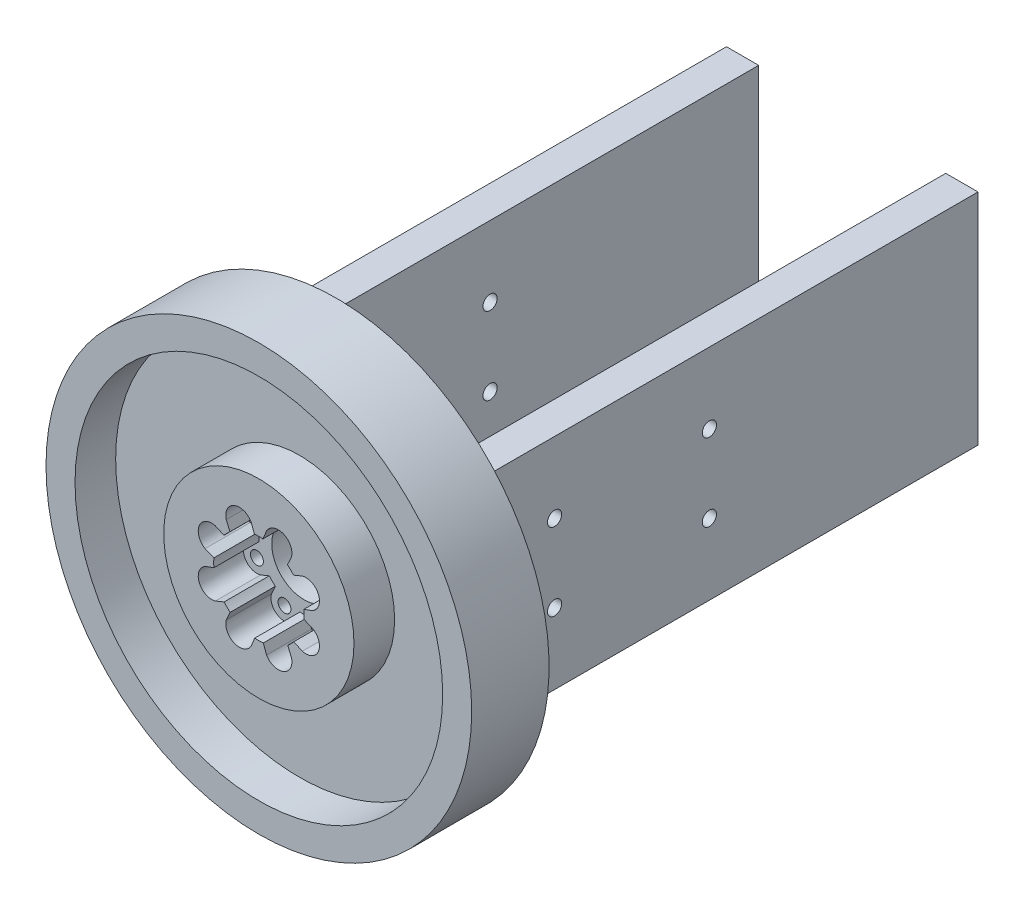
SolidWorks part; units mm, degrees
ref_plane "Alzado" through (0, 0, 0) normal (0, 0, 1) x (1, 0, 0)
ref_plane "Planta" through (0, 0, 0) normal (0, 1, 0) x (1, 0, 0)
ref_plane "Vista lateral" through (0, 0, 0) normal (1, 0, 0) x (0, 0, -1)
sketch "Croquis1" plane through (0, 0, 0) normal (0, 0, 1) x (1, 0, 0)
  circle A0 centre (0, 0) radius 33
  dimension "D1" = 66
extrude "Saliente-Extruir3" add sketch "Croquis1" along normal blind 10
sketch "Croquis6" plane through (0, 0, 0) normal (0, 0, -1) x (-1, 0, 0)
  circle A1 centre (0, 0) radius 28 construction
  circle A2 centre (0, 28) radius 1.5
  circle A3 centre (24.2487, 14) radius 1.5
  circle A4 centre (24.2487, -14) radius 1.5
  circle A5 centre (0, -28) radius 1.5
  circle A6 centre (-24.2487, -14) radius 1.5
  circle A7 centre (-24.2487, 14) radius 1.5
  dimension "D1" = 56
  dimension "D2" = 3
  dimension "D3" = 6
extrude "Cortar-Extruir4" cut sketch "Croquis6" against normal blind 2
sketch "Croquis7" plane through (0, 0, 0) normal (0, 0, -1) x (-1, 0, 0)
  circle A0 centre (0, 0) radius 11
  circle A1 centre (0, 0) radius 33
  circle A2 centre (0, 0) radius 33
  circle A3 centre (24.2487, -14) radius 1.5 construction
  circle A4 centre (0, -28) radius 1.5 construction
  circle A5 centre (-24.2487, -14) radius 1.5 construction
  circle A6 centre (24.2487, 14) radius 1.5 construction
  circle A7 centre (0, 28) radius 1.5 construction
  circle A8 centre (-24.2487, 14) radius 1.5 construction
  circle A9 centre (24.2487, -14) radius 1.5
  circle A10 centre (0, -28) radius 1.5
  circle A11 centre (-24.2487, -14) radius 1.5
  circle A12 centre (24.2487, 14) radius 1.5
  circle A13 centre (0, 28) radius 1.5
  circle A14 centre (-24.2487, 14) radius 1.5
  dimension "D2" = 22
  dimension "D1" = 0
extrude "Saliente-Extruir5" add sketch "Croquis7" along normal blind 2
sketch "Croquis8" plane through (0, 0, -2) normal (0, 0, -1) x (-1, 0, 0)
  line L0 (0, 33) -> (0, -33) construction
  line L1 (14.5, 0) -> (-14.5, 0) construction
  line L3 (-19.5, -17) -> (-14.5, -17)
  line L4 (-19.5, -17) -> (-19.5, 17)
  line L5 (-19.5, 17) -> (-14.5, 17)
  line L6 (-14.5, -17) -> (-14.5, 17)
  line L7 (14.5, -17) -> (19.5, -17)
  line L8 (14.5, -17) -> (14.5, 17)
  line L9 (14.5, 17) -> (19.5, 17)
  line L10 (19.5, -17) -> (19.5, 17)
  circle A0 centre (0, 0) radius 33 construction
  point P8 (0, 0)
  point P16 (-14.5, 0)
  point P17 (14.5, 0)
  dimension "D1" = 29
  dimension "D2" = 34
  dimension "D3" = 34
  dimension "D4" = 5
  dimension "D5" = 5
extrude "Saliente-Extruir6" add sketch "Croquis8" along normal blind 80
fillet "Redondeo1" radius 3 4 edges at (-17, 17, -2) (-17, -17, -2) (17, 17, -2) (17, -17, -2)
sketch "Croquis9" plane through (-19.5, 0, 0) normal (-1, 0, 0) x (0, 0, 1)
  line L0 (-2, 33) -> (-2, -33) construction
  line L2 (-82, 17) -> (-5, 17) construction
  circle A0 centre (-16.35, 6) radius 1.1
  circle A1 centre (-16.35, -6) radius 1.1
  circle A2 centre (-40.35, 6) radius 1.1
  circle A3 centre (-40.35, -6) radius 1.1
  dimension "D1" = 2.2
  dimension "D2" = 14.35
  dimension "D3" = 12
  dimension "D4" = 11
  dimension "D5" = 24
extrude "Cortar-Extruir5" cut sketch "Croquis9" against normal up to surface (39 mm away) up to face at (19.5, 0, -29.4596)
sketch "Croquis10" plane through (0, 0, -2) normal (0, 0, -1) x (-1, 0, 0)
  line L0 (14.5, 20) -> (14.5, 17) construction
  line L1 (-14.5, -17) -> (14.5, -17)
  line L2 (-14.5, -17) -> (-14.5, 17)
  line L3 (-14.5, 17) -> (14.5, 17)
  line L4 (14.5, -17) -> (14.5, 17)
  line L5 (-14.5, 17) -> (-19.5, 17) construction
  line L6 (14.5, -17) -> (19.5, -17) construction
  line L7 (-14.5, -20) -> (-14.5, 20) construction
  circle A0 centre (0, 0) radius 11
  dimension "D1" = 22
extrude "Saliente-Extruir7" add sketch "Croquis10" along normal blind 7.1
fillet "Redondeo2" radius 3 2 edges at (0, 17, -2) (0, -17, -2)
sketch "Croquis12" plane through (0, 0, -82) normal (0, 0, -1) x (-1, 0, 0)
  line L0 (-14.5, 17) -> (-19.5, 17) construction
  line L1 (19.5, -20) -> (19.5, 20) construction
  line L2 (-19.5, -17) -> (-14.5, -17) construction
  circle A0 centre (-17, 14.5) radius 1.1002
  circle A1 centre (-17, -14.5) radius 1.1002
  circle A2 centre (17, -14.5) radius 1.1002
  circle A3 centre (17, 14.5) radius 1.1002
  point P10 (-17, 17)
  dimension "D1" = 2.2003
  dimension "D2" = 2.5
  dimension "D3" = 2.5
  dimension "D4" = 2.5
extrude "Cortar-Extruir6" cut sketch "Croquis12" against normal blind 10
sketch "Croquis13" plane through (0, 0, 10) normal (0, 0, 1) x (1, 0, 0)
  circle A0 centre (0, 0) radius 28.5
  circle A1 centre (0, 0) radius 14.75
  dimension "D1" = 57
  dimension "D2" = 29.5
extrude "Cortar-Extruir7" cut sketch "Croquis13" against normal blind 6.3
sketch "Croquis16" plane through (0, 0, -9.1) normal (0, 0, -1) x (-1, 0, 0)
  line L0 (14.5, -20) -> (-14.5, -20) construction
  line L1 (-5, -9.798) -> (5, -9.798)
  line L2 (-5, -9.798) -> (-5, -20)
  line L3 (-5, -20) -> (5, -20)
  line L4 (5, -9.798) -> (5, -20)
  circle A0 centre (0, 0) radius 11 construction
  point P12 (0, -9.798)
  dimension "D1" = 10
extrude "Cortar-Extruir11" cut sketch "Croquis16" against normal blind 4
sketch "Croquis19" plane through (0, 0, 10) normal (0, 0, 1) x (1, 0, 0)
  line L16 (6.734, 5.0459) -> (5.3759, 4.4833)
  line L17 (4.4391, 5.4124) -> (5.0481, 6.742)
  line L18 (1.1937, 8.3296) -> (0.6311, 6.9715)
  line L19 (-0.6883, 6.9661) -> (-1.1978, 8.3369)
  line L20 (-5.0459, 6.734) -> (-4.4833, 5.3759)
  line L21 (-5.4124, 4.4391) -> (-6.742, 5.0481)
  line L22 (-8.3296, 1.1937) -> (-6.9715, 0.6311)
  line L23 (-6.9661, -0.6883) -> (-8.3369, -1.1978)
  line L24 (-6.734, -5.0459) -> (-5.3759, -4.4833)
  line L25 (-4.4391, -5.4124) -> (-5.0481, -6.742)
  line L26 (-1.1937, -8.3296) -> (-0.6311, -6.9715)
  line L27 (0.6883, -6.9661) -> (1.1978, -8.3369)
  line L28 (5.0459, -6.734) -> (4.4833, -5.3759)
  line L29 (5.4124, -4.4391) -> (6.742, -5.0481)
  line L30 (8.3296, -1.1937) -> (6.9715, -0.6311)
  line L31 (6.9661, 0.6883) -> (8.3369, 1.1978)
  line L32 (6.8956, 4.5716) -> (5.2175, 3.8765) construction
  line L33 (6.4197, 1.0186) -> (8.1222, 1.6514) construction
  line L34 (8.1085, -1.6433) -> (6.4305, -0.9482) construction
  line L35 (5.2597, -3.8191) -> (6.911, -4.5755) construction
  line L36 (4.5716, -6.8956) -> (3.8765, -5.2175) construction
  line L37 (1.0186, -6.4197) -> (1.6514, -8.1222) construction
  line L38 (-1.6433, -8.1085) -> (-0.9482, -6.4305) construction
  line L39 (-3.8191, -5.2597) -> (-4.5755, -6.911) construction
  line L40 (-6.8956, -4.5716) -> (-5.2175, -3.8765) construction
  line L41 (-6.4197, -1.0186) -> (-8.1222, -1.6514) construction
  line L42 (-8.1085, 1.6433) -> (-6.4305, 0.9482) construction
  line L43 (-5.2597, 3.8191) -> (-6.911, 4.5755) construction
  line L44 (-4.5716, 6.8956) -> (-3.8765, 5.2175) construction
  line L45 (-1.0186, 6.4197) -> (-1.6514, 8.1222) construction
  line L46 (1.6433, 8.1085) -> (0.9482, 6.4305) construction
  line L47 (3.8191, 5.2597) -> (4.5755, 6.911) construction
  arc A16 (5.3759, 4.4833) -> (4.4391, 5.4124) centre (0, 0) ccw
  arc A17 (5.0481, 6.742) -> (1.1937, 8.3296) centre (3.0232, 7.2986) ccw
  arc A18 (0.6311, 6.9715) -> (-0.6883, 6.9661) centre (0, 0) ccw
  arc A19 (-1.1978, 8.3369) -> (-5.0459, 6.734) centre (-3.0232, 7.2986) ccw
  arc A20 (-4.4833, 5.3759) -> (-5.4124, 4.4391) centre (0, 0) ccw
  arc A21 (-6.742, 5.0481) -> (-8.3296, 1.1937) centre (-7.2986, 3.0232) ccw
  arc A22 (-6.9715, 0.6311) -> (-6.9661, -0.6883) centre (0, 0) ccw
  arc A23 (-8.3369, -1.1978) -> (-6.734, -5.0459) centre (-7.2986, -3.0232) ccw
  arc A24 (-5.3759, -4.4833) -> (-4.4391, -5.4124) centre (0, 0) ccw
  arc A25 (-5.0481, -6.742) -> (-1.1937, -8.3296) centre (-3.0232, -7.2986) ccw
  arc A26 (-0.6311, -6.9715) -> (0.6883, -6.9661) centre (0, 0) ccw
  arc A27 (1.1978, -8.3369) -> (5.0459, -6.734) centre (3.0232, -7.2986) ccw
  arc A28 (4.4833, -5.3759) -> (5.4124, -4.4391) centre (0, 0) ccw
  arc A29 (6.742, -5.0481) -> (8.3296, -1.1937) centre (7.2986, -3.0232) ccw
  arc A30 (6.9715, -0.6311) -> (6.9661, 0.6883) centre (0, 0) ccw
  arc A31 (8.3369, 1.1978) -> (6.734, 5.0459) centre (7.2986, 3.0232) ccw
  arc A32 (5.2175, 3.8765) -> (3.8191, 5.2597) centre (0, 0) ccw construction
  arc A33 (8.1222, 1.6514) -> (6.8956, 4.5716) centre (7.2986, 3.0232) ccw construction
  arc A34 (6.4305, -0.9482) -> (6.4197, 1.0186) centre (0, 0) ccw construction
  arc A35 (6.911, -4.5755) -> (8.1085, -1.6433) centre (7.2986, -3.0232) ccw construction
  arc A36 (3.8765, -5.2175) -> (5.2597, -3.8191) centre (0, 0) ccw construction
  arc A37 (1.6514, -8.1222) -> (4.5716, -6.8956) centre (3.0232, -7.2986) ccw construction
  arc A38 (-0.9482, -6.4305) -> (1.0186, -6.4197) centre (0, 0) ccw construction
  arc A39 (-4.5755, -6.911) -> (-1.6433, -8.1085) centre (-3.0232, -7.2986) ccw construction
  arc A40 (-5.2175, -3.8765) -> (-3.8191, -5.2597) centre (0, 0) ccw construction
  arc A41 (-8.1222, -1.6514) -> (-6.8956, -4.5716) centre (-7.2986, -3.0232) ccw construction
  arc A42 (-6.4305, 0.9482) -> (-6.4197, -1.0186) centre (0, 0) ccw construction
  arc A43 (-6.911, 4.5755) -> (-8.1085, 1.6433) centre (-7.2986, 3.0232) ccw construction
  arc A44 (-3.8765, 5.2175) -> (-5.2597, 3.8191) centre (0, 0) ccw construction
  arc A45 (-1.6514, 8.1222) -> (-4.5716, 6.8956) centre (-3.0232, 7.2986) ccw construction
  arc A46 (0.9482, 6.4305) -> (-1.0186, 6.4197) centre (0, 0) ccw construction
  arc A47 (4.5755, 6.911) -> (1.6433, 8.1085) centre (3.0232, 7.2986) ccw construction
  dimension "D1" = 0.5
extrude "Cortar-Extruir15" cut sketch "Croquis19" against normal blind 7
sketch "Croquis20" plane through (0, 0, 3) normal (0, 0, 1) x (1, 0, 0)
  circle A8 centre (-7.2986, 3.0232) radius 1
  circle A9 centre (-7.2986, -3.0232) radius 1
  circle A10 centre (-3.0232, -7.2986) radius 1
  circle A11 centre (3.0232, -7.2986) radius 1
  circle A12 centre (7.2986, -3.0232) radius 1
  circle A13 centre (7.2986, 3.0232) radius 1
  circle A14 centre (3.0232, 7.2986) radius 1
  circle A15 centre (-3.0232, 7.2986) radius 1
extrude "Cortar-Extruir16" cut sketch "Croquis20" against normal up to next
sketch "Croquis21" plane through (0, 0, 3) normal (0, 0, 1) x (1, 0, 0)
  circle A0 centre (0, 0) radius 5
  dimension "D1" = 10
extrude "Cortar-Extruir17" cut sketch "Croquis21" against normal up to next contours A0
